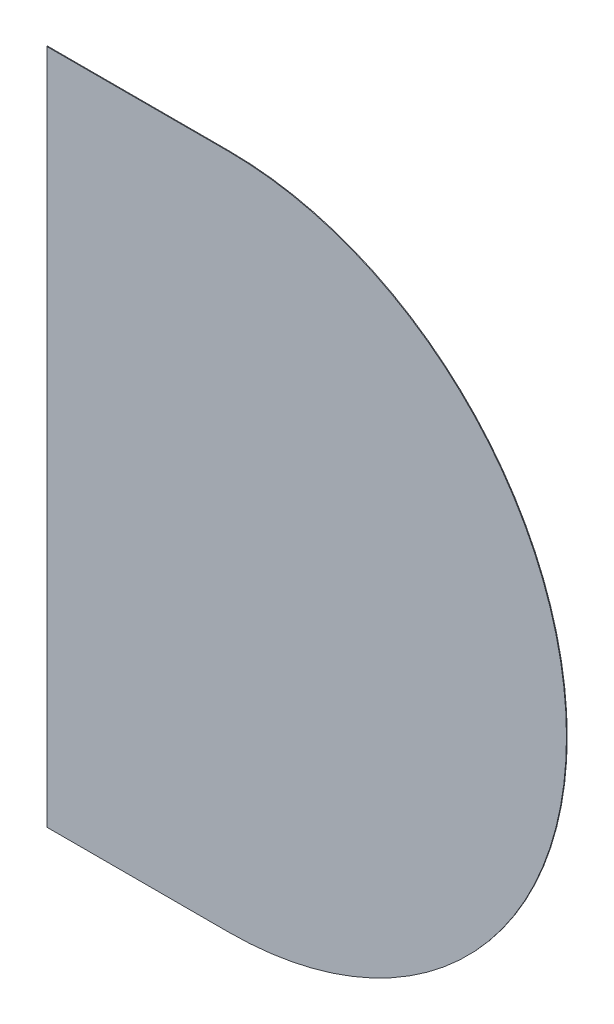
SolidWorks part; units mm, degrees
ref_plane "Front Plane" through (0, 0, 0) normal (0, 0, 1) x (1, 0, 0)
ref_plane "Top Plane" through (0, 0, 0) normal (0, 1, 0) x (1, 0, 0)
ref_plane "Right Plane" through (0, 0, 0) normal (1, 0, 0) x (0, 0, -1)
sketch "Sketch1" plane through (0, 0, 0) normal (0, 0, 1) x (1, 0, 0)
  line L1 (0, 0) -> (485, 0)
  line L2 (0, 0) -> (0, 1805)
  line L3 (0, 1805) -> (485, 1805)
  line L4 (485, 0) -> (485, 1805) construction
  arc A0 (485, 1805) -> (485, 0) centre (485, 902.5) cw
  dimension "D1" = 485
  dimension "D2" = 1805
extrude "Boss-Extrude1" add sketch "Sketch1" along normal blind 2
